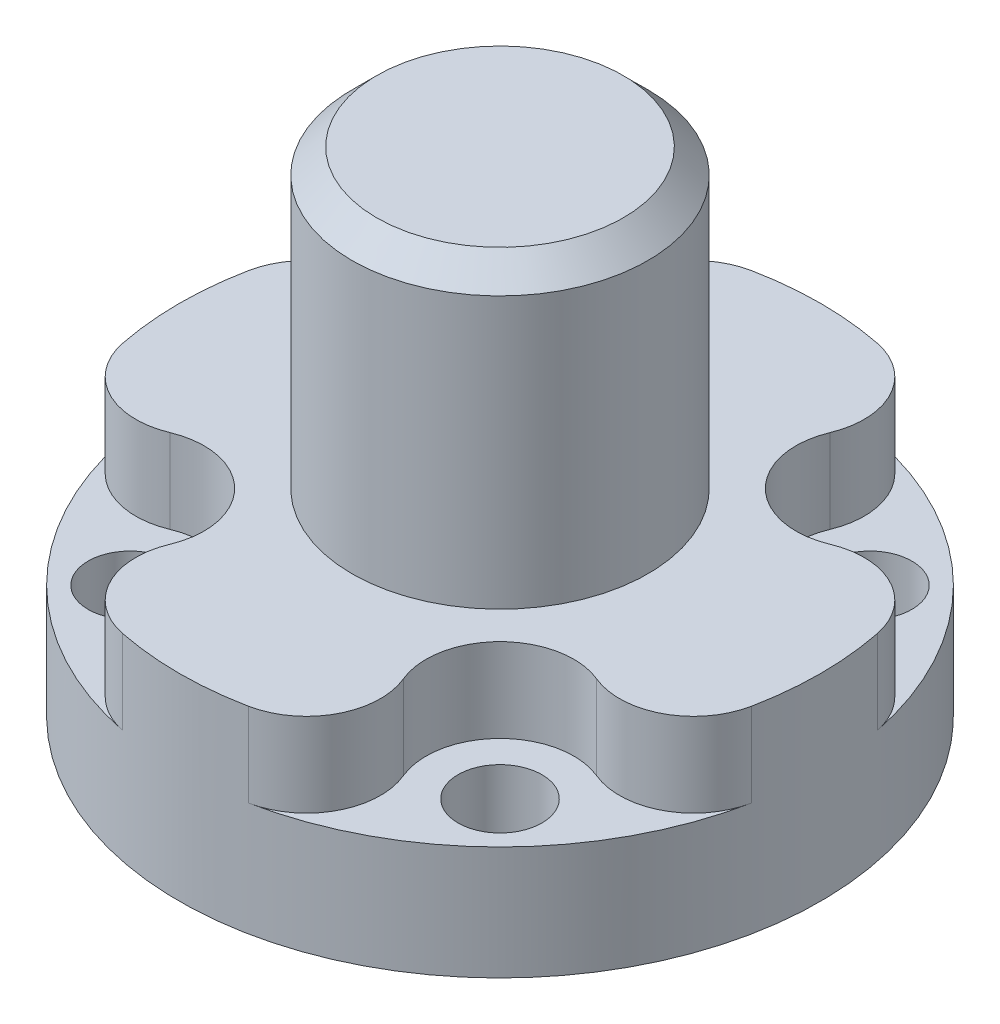
SolidWorks part; units mm, degrees
material "6061 Alloy"
ref_plane "Front Plane" through (0, 0, 0) normal (0, 0, 1) x (1, 0, 0)
ref_plane "Top Plane" through (0, 0, 0) normal (0, 1, 0) x (1, 0, 0)
ref_plane "Right Plane" through (0, 0, 0) normal (1, 0, 0) x (0, 0, -1)
sketch "Sketch1" plane through (0, 0, 0) normal (0, 1, 0) x (1, 0, 0)
  circle A0 centre (0, 0) radius 6
  dimension "D1" = 12
extrude "Boss-Extrude1" add sketch "Sketch1" along normal blind 20
sketch "Sketch3" plane through (0, 0, 0) normal (0, -1, 0) x (1, 0, 0)
  circle A0 centre (0, 0) radius 13
  dimension "D1" = 26
extrude "Boss-Extrude2" add sketch "Sketch3" against normal blind 8
sketch "Sketch2" plane through (0, 0, 0) normal (0, -1, 0) x (1, 0, 0)
  circle A0 centre (0, 0) radius 3
  dimension "D1" = 6
extrude "Cut-Extrude1" [suppressed] cut sketch "Sketch2" against normal through all
hole_wizard "CBORE for M3 Hexagon socket head cap screws1" positions "Sketch4" profile "Sketch5" counterbore size "M3" standard "GB" end condition through all
sketch "Sketch4" plane through (0, 8, 0) normal (0, 1, 0) x (1, 0, 0)
  line L0 (-11, 0) -> (11, 0) construction
  line L1 (0, -11) -> (0, 11) construction
  point P0 (-7.5, 7.5)
  point P5 (-7.5, -7.5)
  point P8 (7.5, -7.5)
  point P9 (7.5, 7.5)
  dimension "D1" = 15
  dimension "D2" = 15
sketch "Sketch5" plane through (-7.5, 8, -7.5) normal (1, 0, 0) x (0, 0, 1)
  line L0 (0, 0) -> (0, 8)
  line L1 (0, 8) -> (1.7, 8)
  line L3 (1.7, 8) -> (1.7, 3.4)
  line L4 (1.7, 3.4) -> (3, 3.4)
  line L5 (3, 3.4) -> (3, 0)
  line L7 (3, 0) -> (0, 0)
  line L11 (0, -6.35) -> (0, 107.95) construction
  dimension "Thru Hole Dia." = 3.4
  dimension "Thru Hole Depth" = 8
  dimension "C'Bore Dia." = 6
  dimension "C'Bore Depth" = 3.4
fillet "Fillet1" radius 3 8 edges at (10.4951, 6.3, -7.6716) (7.6716, 6.3, -10.4951) (7.6716, 6.3, 10.4951) (10.4951, 6.3, 7.6716) (-10.4951, 6.3, 7.6716) (-7.6716, 6.3, 10.4951) (-7.6716, 6.3, -10.4951) (-10.4951, 6.3, -7.6716)
chamfer "Chamfer1" distance 1 angle 45 1 edges at (0, 20, 6)
sketch "Sketch6" plane through (0, 0, 0) normal (1, 0, 0) x (0, 0, -1)
  circle A0 centre (0, 27) radius 1.5
  dimension "D1" = 3
  dimension "D2" = 27
extrude "Cut-Extrude2" [suppressed] cut sketch "Sketch6" against normal through all both and the other way through all
sketch "Sketch7" plane through (0, 0, 0) normal (0, -1, 0) x (1, 0, 0)
  circle A0 centre (0, 0) radius 3
  dimension "D1" = 6
extrude "Boss-Extrude3" add sketch "Sketch7" along normal blind 5
chamfer "Chamfer2" distance 1 angle 45 1 edges at (0, -5, -3)
